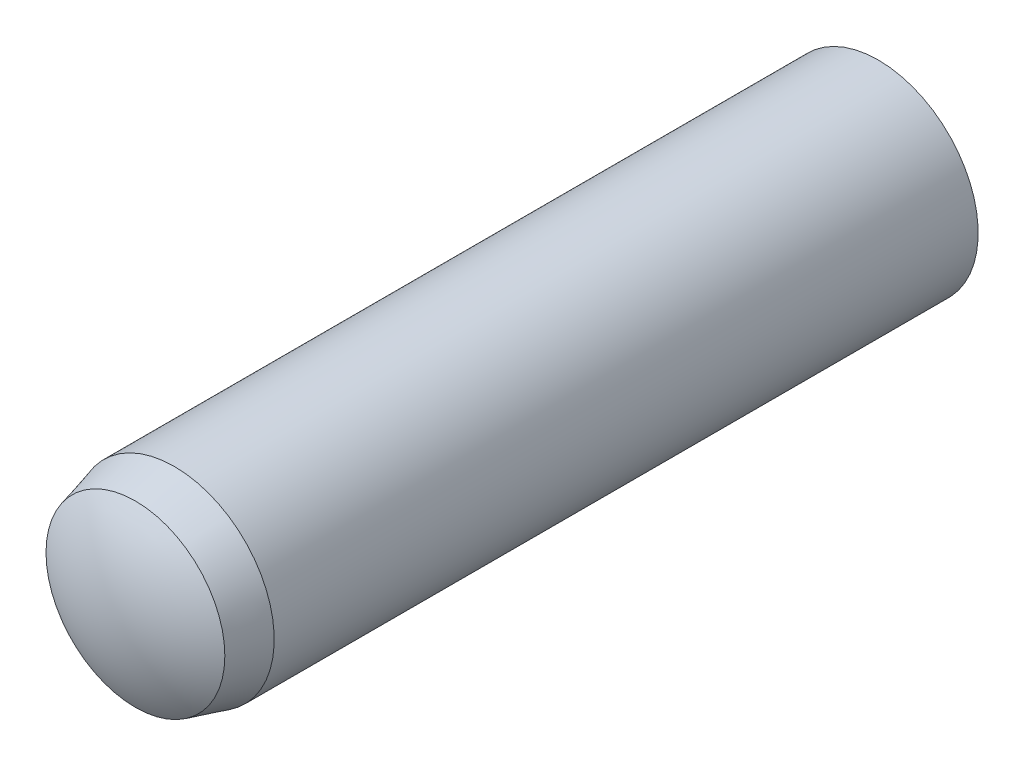
SolidWorks part; units mm, degrees
ref_plane "Front Plane" through (0, 0, 0) normal (0, 0, 1) x (1, 0, 0)
ref_plane "Top Plane" through (0, 0, 0) normal (0, 1, 0) x (1, 0, 0)
ref_plane "Right Plane" through (0, 0, 0) normal (1, 0, 0) x (0, 0, -1)
sketch "Sketch1" plane through (0, 0, 0) normal (0, 0, 1) x (1, 0, 0)
  circle A0 centre (0, 0) radius 5
  point P3 (0, 5)
  dimension "Diameter" = 10
sketch "Sketch2" plane through (0, 0, 0) normal (1, 0, 0) x (0, 0, -1)
  line L0 (-20, 0) -> (20, 0) construction
  line L1 (-20, 0) -> (-20, 5) construction
  line L2 (-20, 5) -> (20, 5)
  line L3 (20, 5) -> (20, 0) construction
  line L4 (-18.7, 4.4775) -> (-16.75, 5)
  arc A0 (-20, 0) -> (-18.7, 4.4775) centre (-11.6392, 0) cw
  arc A1 (20, 0) -> (18.5, 5) centre (10.9167, 0) ccw
  point P2 (0, 0)
  point P11 (-10, 0)
  point P13 (10, 0)
  dimension "Length" = 40
  dimension "D1" = 15
  dimension "D2" = 1.5
  dimension "D3" = 3.25
  dimension "D4" = 1.95
  dimension "D5" = 10
  dimension "D6" = 10
sketch "Sketch3" plane through (0, 0, 0) normal (1, 0, 0) x (0, 0, -1)
  line L0 (-20, 0) -> (20, 0) construction
  line L1 (-18.7, 4.4775) -> (-16.75, 5) construction
  line L2 (-20, 0) -> (20, 0)
  line L3 (-18.7, 4.4775) -> (-16.75, 5)
  line L4 (-16.75, 5) -> (18.5, 5)
  arc A0 (20, 0) -> (18.5, 5) centre (10.9167, 0) ccw construction
  arc A1 (-18.7, 4.4775) -> (-20, 0) centre (-11.6392, 0) ccw construction
  arc A2 (20, 0) -> (18.5, 5) centre (10.9167, 0) ccw
  arc A3 (-18.7, 4.4775) -> (-20, 0) centre (-11.6392, 0) ccw
revolve "Revolve1" add sketch "Sketch3" angle 360 about L2
equation "\"D2@Sketch2\" = \"Diameter@Sketch1\" * .15"
equation "\"D3@Sketch2\" = \"Diameter@Sketch1\" * .325"
equation "\"D4@Sketch2\" = \"D3@Sketch2\" * .6"
equation "\"D5@Sketch2\"=\"Diameter@Sketch1\""
equation "\"D6@Sketch2\"=\"D5@sketch2\""
